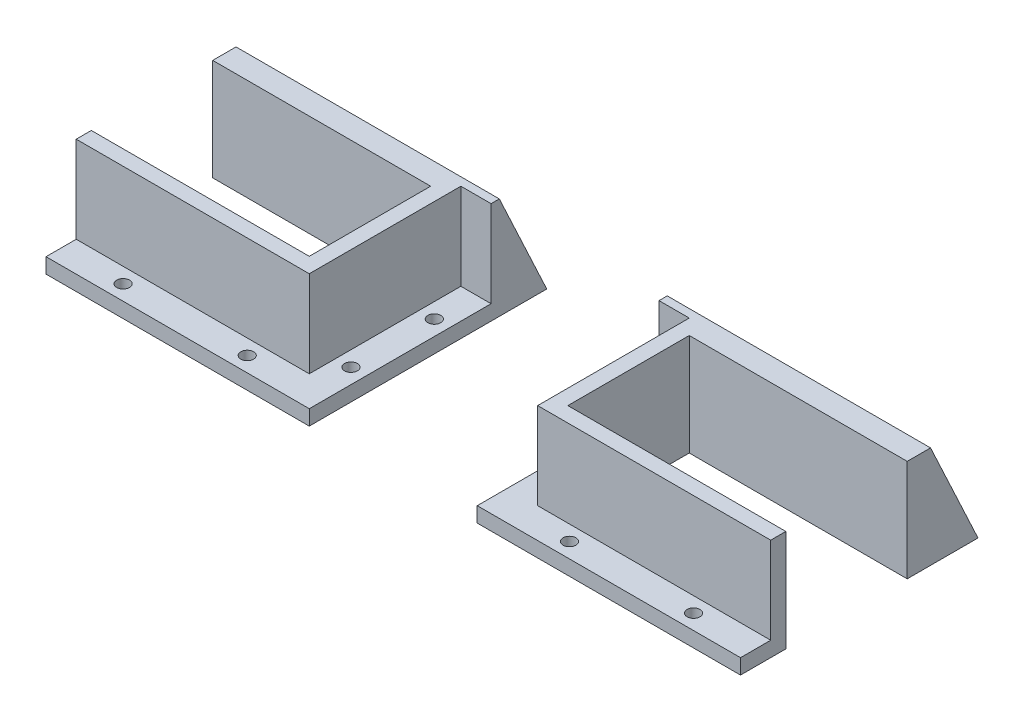
SolidWorks part; units mm, degrees
material "PLA"
ref_plane "Front Plane" through (0, 0, 0) normal (0, 0, 1) x (1, 0, 0)
ref_plane "Top Plane" through (0, 0, 0) normal (0, 1, 0) x (1, 0, 0)
ref_plane "Right Plane" through (0, 0, 0) normal (1, 0, 0) x (0, 0, -1)
sketch "Sketch1" plane through (0, 0, 0) normal (0, 1, 0) x (1, 0, 0)
  line L0 (0, 0) -> (0, 26.365) construction
  line L1 (-73, -26.365) -> (73, -26.365) construction
  line L2 (-73, -26.365) -> (-73, 26.365) construction
  line L3 (-73, 26.365) -> (73, 26.365) construction
  line L4 (73, -26.365) -> (73, 26.365) construction
  line L5 (-73, 0) -> (73, 0) construction
  line L6 (-73, 12.76) -> (-27.18, 12.76)
  line L7 (73, 12.56) -> (27.38, 12.56) construction
  line L8 (-27.18, 12.76) -> (-27.18, -12.76)
  line L9 (-27.18, -12.76) -> (-73, -12.76)
  line L10 (73, -12.56) -> (27.38, -12.56) construction
  line L11 (73, 12.56) -> (73, -12.56) construction
  line L12 (39.88, 12.56) -> (39.88, 0) construction
  line L13 (27.38, -12.56) -> (27.38, 12.56) construction
  line L14 (-27.38, 12.56) -> (-73, 12.56) construction
  line L15 (-27.38, -12.56) -> (-73, -12.56) construction
  line L16 (-27.38, 12.56) -> (-27.38, -12.56) construction
  line L17 (-73, -12.56) -> (-73, 12.56) construction
  line L18 (-39.88, 12.56) -> (-39.88, 0) construction
  line L19 (-73, -12.56) -> (-27.38, -12.56) construction
  line L20 (-73, -12.56) -> (-73, 12.56) construction
  line L21 (-73, 12.56) -> (-27.38, 12.56) construction
  line L22 (-27.38, -12.56) -> (-27.38, 12.56) construction
  line L23 (27.38, -12.56) -> (73, -12.56) construction
  line L24 (27.38, -12.56) -> (27.38, 12.56) construction
  line L25 (27.38, 12.56) -> (73, 12.56) construction
  line L26 (73, -12.56) -> (73, 12.56) construction
  line L27 (-73, 12.76) -> (-73, 15.935)
  line L28 (-73, 15.935) -> (-24.005, 15.935)
  line L29 (-24.005, 15.935) -> (-24.005, -15.935)
  line L30 (-24.005, -15.935) -> (-73, -15.935)
  line L31 (-73, -15.935) -> (-73, -12.76)
  line L32 (73, 12.76) -> (27.18, 12.76)
  line L33 (27.18, 12.76) -> (27.18, -12.76)
  line L34 (27.18, -12.76) -> (73, -12.76)
  line L35 (73, -12.76) -> (73, -15.935)
  line L36 (73, -15.935) -> (24.005, -15.935)
  line L37 (24.005, -15.935) -> (24.005, 15.935)
  line L38 (24.005, 15.935) -> (73, 15.935)
  line L39 (73, 15.935) -> (73, 12.76)
  circle A0 centre (39.88, 0) radius 3 construction
  circle A1 centre (-39.88, 0) radius 3 construction
  point P5 (-73, 0)
  point P7 (0, 26.365)
  point P14 (73, 0)
  point P24 (-73, 0)
  point P29 (-27.38, 0)
  point P32 (39.88, 0)
  point P33 (27.38, 0)
  dimension "D6" = 6
  dimension "D10" = 6
  dimension "D1" = 146
  dimension "D2" = 52.73
  dimension "D3" = 45.62
  dimension "D4" = 12.5
  dimension "D5" = 25.12
  dimension "D7" = 25.12
  dimension "D8" = 45.62
  dimension "D9" = 12.5
  dimension "D11" = 0.2
  dimension "D12" = 0.2
  dimension "D13" = 0.2
  dimension "D14" = 0
  dimension "D15" = 0
  dimension "D16" = 3.175
  dimension "D17" = 3.175
  dimension "D18" = 3.175
  dimension "D19" = 0.2
  dimension "D20" = 0.2
  dimension "D21" = 0.2
  dimension "D22" = 3.175
  dimension "D23" = 3.175
  dimension "D24" = 3.175
extrude "Boss-Extrude1" add sketch "Sketch1" along normal blind 21.395
sketch "Sketch2" plane through (0, 0, 0) normal (0, 1, 0) x (1, 0, 0)
  line L0 (20.83, 15.935) -> (20.83, -1.5875) construction
  line L5 (-73, -19.11) -> (-46.915, -19.11) construction
  line L6 (-73, -15.935) -> (-24.005, -15.935)
  line L7 (-73, -15.935) -> (-73, -22.285)
  line L8 (-73, -22.285) -> (-24.005, -22.285)
  line L10 (73, -15.935) -> (24.005, -15.935)
  line L11 (73, -15.935) -> (73, -22.285)
  line L12 (73, -22.285) -> (24.005, -22.285)
  line L15 (24.005, 15.935) -> (17.655, 15.935)
  line L16 (24.005, 15.935) -> (24.005, -15.935)
  line L17 (24.005, -22.285) -> (17.655, -22.285)
  line L18 (17.655, 15.935) -> (17.655, -22.285)
  line L19 (-24.005, 15.935) -> (-17.655, 15.935)
  line L20 (-24.005, 15.935) -> (-24.005, -15.935)
  line L21 (-24.005, -22.285) -> (-17.655, -22.285)
  line L22 (-17.655, 15.935) -> (-17.655, -22.285)
  line L24 (-20.83, 15.935) -> (-20.83, -1.5875) construction
  line L25 (-20.83, -1.5875) -> (-20.83, -19.11) construction
  line L26 (-46.915, -19.11) -> (-20.83, -19.11) construction
  line L27 (20.83, -1.5875) -> (20.83, -19.11) construction
  line L28 (20.83, -19.11) -> (46.915, -19.11) construction
  line L29 (46.915, -19.11) -> (73, -19.11) construction
  circle A6 centre (-20.83, -10.3488) radius 1.35
  circle A7 centre (-20.83, 7.1737) radius 1.35
  circle A8 centre (-59.9575, -19.11) radius 1.35
  circle A9 centre (-33.8725, -19.11) radius 1.35
  circle A10 centre (20.83, 7.1737) radius 1.35
  circle A11 centre (20.83, -10.3488) radius 1.35
  circle A12 centre (33.8725, -19.11) radius 1.35
  circle A13 centre (59.9575, -19.11) radius 1.35
  dimension "D5" = 2.7
  dimension "D6" = 2.7
  dimension "D7" = 2.7
  dimension "D8" = 2.7
  dimension "D9" = 3.175
  dimension "D10" = 2.7
  dimension "D11" = 2.7
  dimension "D12" = 2.7
  dimension "D13" = 2.7
  dimension "D1" = 6.35
  dimension "D2" = 6.35
  dimension "D3" = 6.35
  dimension "D4" = 6.35
extrude "Boss-Extrude2" add sketch "Sketch2" along normal blind 3.175
sketch "Sketch4" plane through (0, 0, 0) normal (0, 1, 0) x (1, 0, 0)
  line L0 (-73, 15.935) -> (-17.655, 15.935)
  line L1 (-17.655, 15.935) -> (-17.655, 27.64)
  line L2 (-17.655, 27.64) -> (-73, 27.64)
  line L3 (-73, 27.64) -> (-73, 15.935)
  line L4 (17.655, 15.935) -> (73, 15.935)
  line L5 (73, 15.935) -> (73, 27.64)
  line L6 (73, 27.64) -> (17.655, 27.64)
  line L7 (17.655, 27.64) -> (17.655, 15.935)
  line L8 (73, 12.76) -> (73, 15.935) construction
  line L9 (73, 15.935) -> (24.005, 15.935) construction
  dimension "D1" = 11.705
  dimension "D2" = 11.705
  dimension "D3" = 55.345
  dimension "D4" = 0
  dimension "D5" = 0
extrude "Boss-Extrude3" add sketch "Sketch4" along normal up to surface (21.395 mm away) up to face at (-49.2962, 21.395, 0)
sketch "Sketch5" plane through (-73, 0, 0) normal (-1, 0, 0) x (0, 0, 1)
  line L0 (-12.76, 21.395) -> (-15.935, 21.395)
  line L1 (-27.64, 0) -> (-17.6633, 21.395)
  line L5 (-27.64, 21.395) -> (-27.64, 0) construction
  line L6 (-27.64, 21.395) -> (-12.76, 21.395) construction
  line L7 (-17.6633, 21.395) -> (-27.64, 21.395)
  line L8 (-27.64, 21.395) -> (-27.64, 0)
  line M8 (-12.76, 21.395) -> (-27.64, 21.395)
  line M9 (-27.64, 21.395) -> (-27.64, 0)
  dimension "D1" = 3.175
  dimension "D2" = 25
extrude "Cut-Extrude1" cut sketch "Sketch5" against normal through all contours L1 M9 M8
